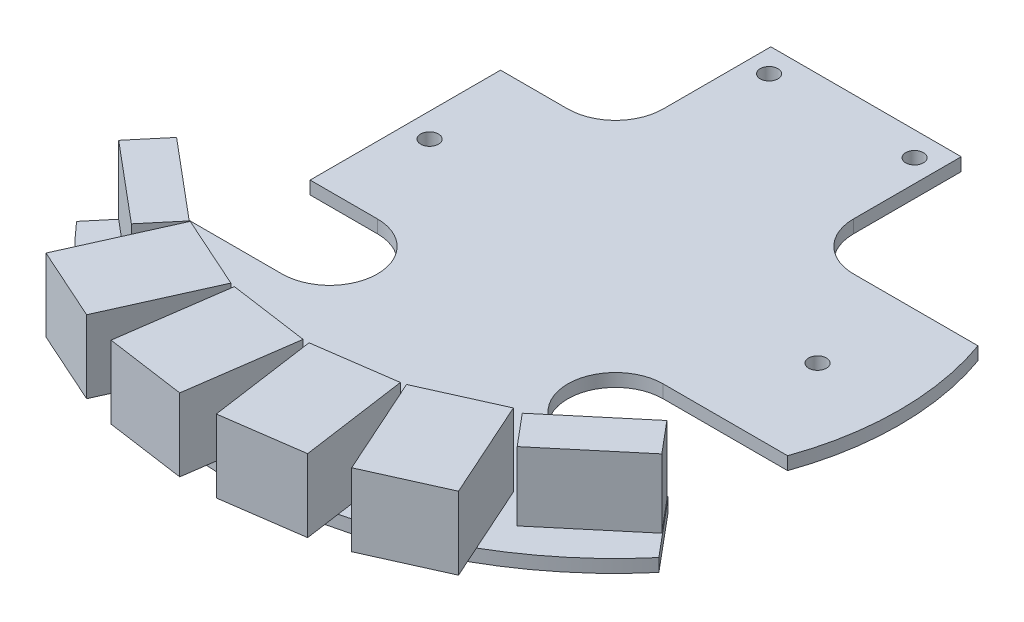
SolidWorks part; units mm, degrees
ref_plane "Front Plane" through (0, 0, 0) normal (0, 0, 1) x (1, 0, 0)
ref_plane "Top Plane" through (0, 0, 0) normal (0, 1, 0) x (1, 0, 0)
ref_plane "Right Plane" through (0, 0, 0) normal (1, 0, 0) x (0, 0, -1)
sketch "Sketch1" plane through (0, 0, 0) normal (0, 1, 0) x (1, 0, 0)
  line L0 (-11.7777, 17.6777) -> (-11.7777, 31)
  line L1 (-17.6777, 11.7777) -> (-26, 11.7777)
  line L2 (17.6777, 11.7777) -> (33.0728, 11.7777)
  line L3 (11.7777, 17.6777) -> (11.7777, 31)
  line L4 (-17.6777, -11.7777) -> (-26, -11.7777)
  line L5 (-17.6777, -23.5777) -> (-30.0977, -23.5777)
  line L6 (17.6777, -11.7777) -> (33.0728, -11.7777)
  line L7 (17.6777, -23.5777) -> (30.0977, -23.5777)
  line L8 (-26, -11.7777) -> (-26, 11.7777)
  line L9 (11.7777, 31) -> (-11.7777, 31)
  line L10 (30.0977, -23.5777) -> (36.0176, -30.6551)
  line L11 (-30.0977, -23.5777) -> (-36.0176, -30.6551)
  arc A0 (11.7777, 17.6777) -> (17.6777, 11.7777) centre (17.6777, 17.6777) ccw
  arc A1 (17.6777, -11.7777) -> (17.6777, -23.5777) centre (17.6777, -17.6777) ccw
  arc A2 (-17.6777, -23.5777) -> (-17.6777, -11.7777) centre (-17.6777, -17.6777) ccw
  arc A3 (-17.6777, 11.7777) -> (-11.7777, 17.6777) centre (-17.6777, 17.6777) ccw
  arc A4 (33.0728, -11.7777) -> (33.0728, 11.7777) centre (0, 0) ccw
  arc A5 (-36.0176, -30.6551) -> (36.0176, -30.6551) centre (0, 0) ccw
  point P24 (-26.5994, 12.4647)
  point P25 (0, 31)
  point P26 (-26, 0)
  point P27 (-36.0176, -30.6551)
  point P29 (-17.6777, -17.6777)
  point P30 (-17.6777, -23.5777)
  point P31 (33.0728, 11.7777)
  point P32 (-11.7777, 31)
  point P33 (11.7777, 31)
  point P34 (0, 0)
  dimension "D1" = 70.2146
  dimension "D2" = 94.594
  dimension "D3" = 12.42
  dimension "D4" = 9.2269
  dimension "D5" = 23.5553
  dimension "D6" = 23.5553
  dimension "D7" = 15.3951
  dimension "D8" = 13.3223
  dimension "D9" = 8.3223
extrude "Boss-Extrude1" add sketch "Sketch1" along normal blind 1.6
sketch "Sketch2" plane through (0, 1.6, 0) normal (0, 1, 0) x (1, 0, 0)
  line L0 (-33.5971, -27.8641) -> (-23.8683, -36.0275)
  line L1 (-33.5971, -27.8641) -> (-30.3317, -23.9725)
  line L2 (-23.8683, -36.0275) -> (-20.6029, -32.1359)
  line L3 (-30.3317, -23.9725) -> (-20.6029, -32.1359)
  line L4 (23.8683, -36.0275) -> (33.5971, -27.8641)
  line L5 (23.8683, -36.0275) -> (20.6029, -32.1359)
  line L6 (33.5971, -27.8641) -> (30.3317, -23.9725)
  line L7 (20.6029, -32.1359) -> (30.3317, -23.9725)
  line L8 (-25.4673, -28.0542) -> (-27.1, -30) construction
  line L9 (-27.1, -30) -> (-22.2356, -34.0817) construction
  line L10 (25.4673, -28.0542) -> (27.1, -30) construction
  line L11 (27.1, -30) -> (22.2356, -34.0817) construction
  line L12 (-27.1, -30) -> (27.1, -30) construction
  point P14 (0, -30)
  dimension "D1" = 12.7
  dimension "D2" = 5.08
  dimension "D3" = 27.1
  dimension "D4" = 30
  dimension "D5" = 50
  dimension "D6" = 50
extrude "Boss-Extrude2" add sketch "Sketch2" along normal blind 8.5
sketch "Sketch3" plane through (0, 1.6, 0) normal (0, 1, 0) x (1, 0, 0)
  line L0 (-25.5179, -44.9397) -> (-19.9902, -32.6233)
  line L1 (-25.5179, -44.9397) -> (-16.3947, -49.0343)
  line L2 (-19.9902, -32.6233) -> (-10.8669, -36.7179)
  line L3 (-16.3947, -49.0343) -> (-10.8669, -36.7179)
  line L4 (-0.3692, -38.2828) -> (-2.2613, -51.6495)
  line L5 (-0.3692, -38.2828) -> (-10.2705, -36.8812)
  line L6 (-2.2613, -51.6495) -> (-12.1626, -50.2479)
  line L7 (-10.2705, -36.8812) -> (-12.1626, -50.2479)
  line L8 (2.2613, -51.6495) -> (0.3692, -38.2828)
  line L9 (2.2613, -51.6495) -> (12.1626, -50.2479)
  line L10 (0.3692, -38.2828) -> (10.2705, -36.8812)
  line L11 (12.1626, -50.2479) -> (10.2705, -36.8812)
  line L12 (16.3947, -49.0343) -> (10.8669, -36.7179)
  line L13 (16.3947, -49.0343) -> (25.5179, -44.9397)
  line L14 (10.8669, -36.7179) -> (19.9902, -32.6233)
  line L15 (25.5179, -44.9397) -> (19.9902, -32.6233)
  line L16 (-5.3198, -37.582) -> (-6.2, -43.8) construction
  line L17 (-6.2, -43.8) -> (-5.0634, -43.9609) construction
  line L18 (5.3198, -37.582) -> (6.2, -43.8) construction
  line L19 (6.2, -43.8) -> (5.0634, -43.9609) construction
  line L20 (15.4286, -34.6706) -> (18, -40.4) construction
  line L21 (18, -40.4) -> (13.4384, -42.4473) construction
  line L22 (-15.4286, -34.6706) -> (-18, -40.4) construction
  line L23 (-18, -40.4) -> (-22.5616, -38.3527) construction
  line L24 (-18, -40.4) -> (18, -40.4) construction
  line L25 (-6.2, -43.8) -> (6.2, -43.8) construction
  point P28 (0, 0)
  point P29 (0, -43.8)
  point P30 (0, -40.4)
  point P32 (-22.7621, -22.4464)
  dimension "D1" = 98.057
  dimension "D2" = 81.943
  dimension "D3" = 13.5
  dimension "D4" = 10
  dimension "D5" = 65.829
  dimension "D6" = 65.829
  dimension "D7" = 6.28
  dimension "D8" = 36
  dimension "D9" = 12.4
  dimension "D10" = 3.4
  dimension "D11" = 40.4
extrude "Boss-Extrude3" add sketch "Sketch3" along normal blind 9
sketch "Sketch4" plane through (0, 1.6, 0) normal (0, 1, 0) x (1, 0, 0)
  line L0 (-9, 28) -> (9, 28) construction
  circle A0 centre (0, -34.8) radius 1.1
  circle A1 centre (25, 0) radius 1.1
  circle A2 centre (-23, 0) radius 1.1
  circle A3 centre (-9, 28) radius 1.1
  circle A4 centre (9, 28) radius 1.1
  point P10 (0, 28)
  point P11 (0, 0)
  point P13 (0, 0)
  point P14 (0, 0)
  point P15 (0, 0)
  dimension "D1" = 2.2
  dimension "D2" = 9
  dimension "D3" = 28
  dimension "D4" = 23
  dimension "D5" = 25
  dimension "D6" = 34.8
extrude "Cut-Extrude1" cut sketch "Sketch4" against normal through all
